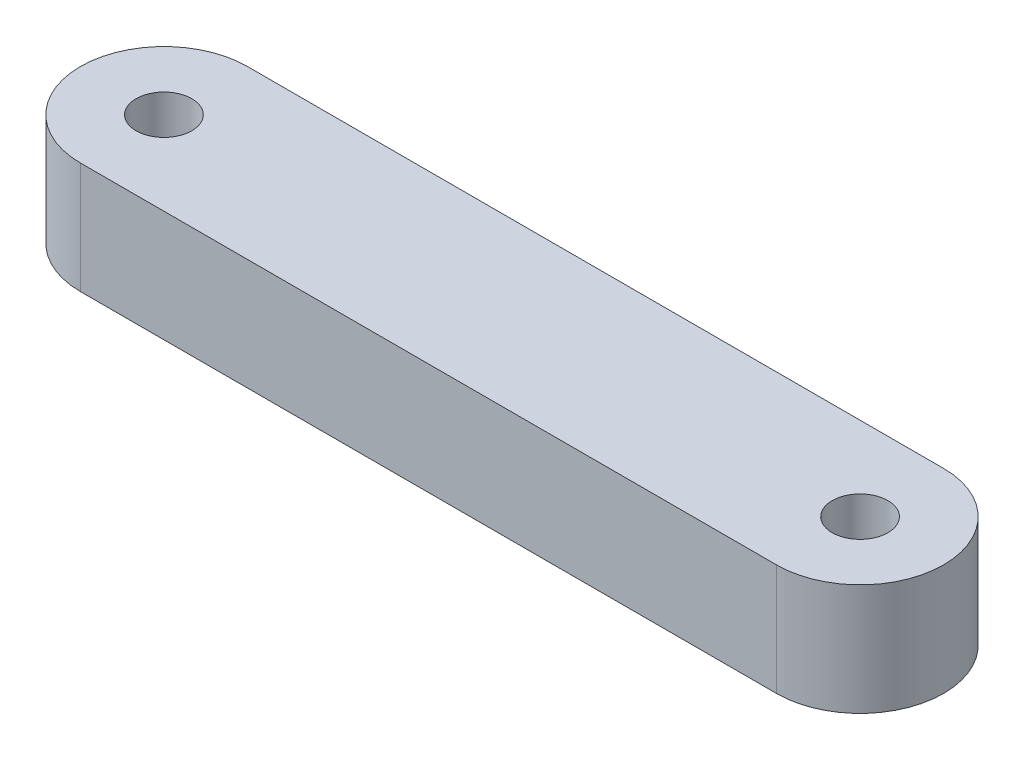
SolidWorks part; units mm, degrees
ref_plane "Front Plane" through (0, 0, 0) normal (0, 0, 1) x (1, 0, 0)
ref_plane "Top Plane" through (0, 0, 0) normal (0, 1, 0) x (1, 0, 0)
ref_plane "Right Plane" through (0, 0, 0) normal (1, 0, 0) x (0, 0, -1)
sketch "Sketch1" plane through (0, 0, 0) normal (0, 1, 0) x (1, 0, 0)
  line L0 (0, 0) -> (25, 0) construction
  line L1 (0, 3) -> (25, 3)
  line L2 (0, -3) -> (25, -3)
  arc A0 (0, 3) -> (0, -3) centre (0, 0) ccw
  arc A1 (25, -3) -> (25, 3) centre (25, 0) ccw
  circle A2 centre (25, 0) radius 1
  circle A3 centre (0, 0) radius 1
  point P3 (12.5, 0)
  dimension "D2" = 3
  dimension "D1" = 25
extrude "Boss-Extrude1" add sketch "Sketch1" along normal blind 4
